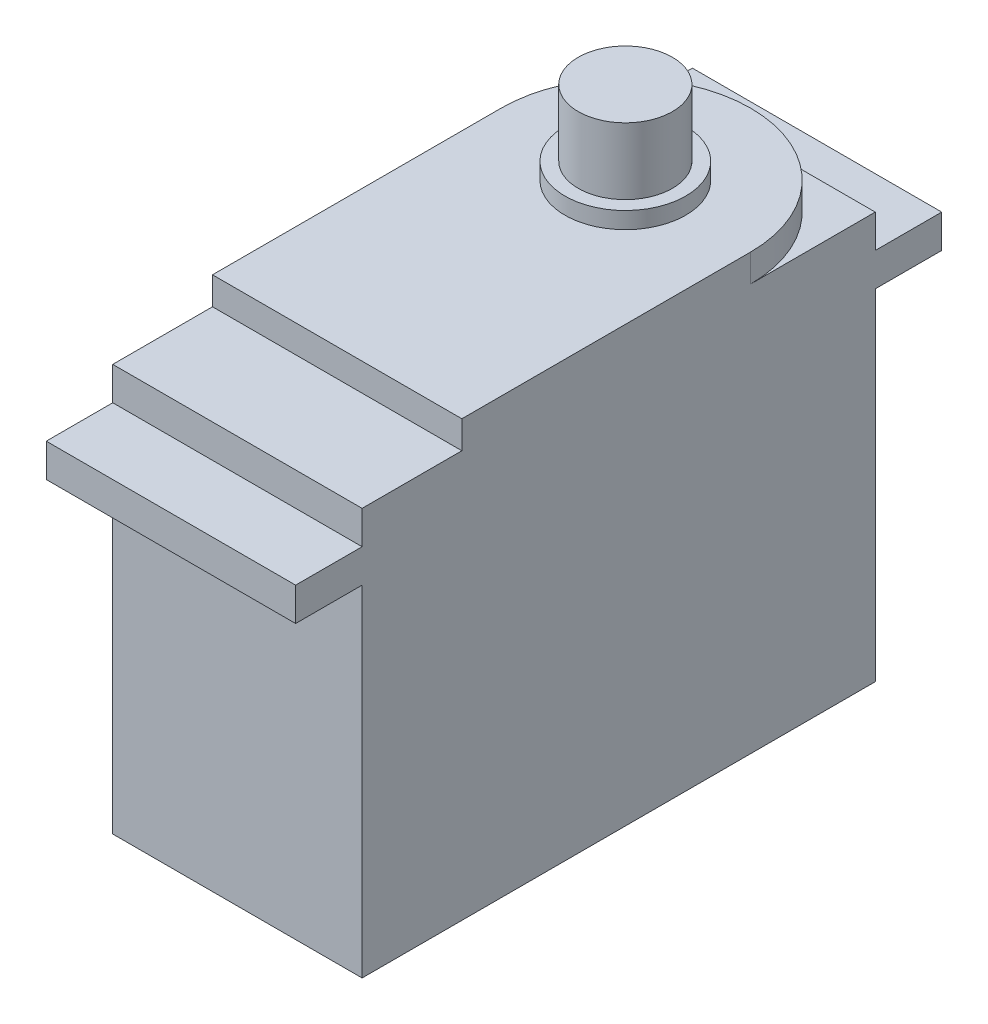
SolidWorks part; units mm, degrees
ref_plane "Front Plane" through (0, 0, 0) normal (0, 0, 1) x (1, 0, 0)
ref_plane "Top Plane" through (0, 0, 0) normal (0, 1, 0) x (1, 0, 0)
ref_plane "Right Plane" through (0, 0, 0) normal (1, 0, 0) x (0, 0, -1)
sketch "Sketch2" plane through (0, 0, 0) normal (0, 1, 0) x (1, 0, 0)
  line L1 (-14.2875, -29.4005) -> (14.2875, -29.4005)
  line L2 (-14.2875, -29.4005) -> (-14.2875, 29.4005)
  line L3 (-14.2875, 29.4005) -> (14.2875, 29.4005)
  line L4 (14.2875, -29.4005) -> (14.2875, 29.4005)
  line L5 (-14.2875, -29.4005) -> (14.2875, 29.4005) construction
  line L6 (-14.2875, 29.4005) -> (14.2875, -29.4005) construction
  point P0 (0, 0)
  dimension "D1" = 28.575
  dimension "D2" = 58.801
extrude "Boss-Extrude1" add sketch "Sketch2" along normal blind 46.609
sketch "Sketch3" plane through (0, 46.609, 0) normal (0, 1, 0) x (1, 0, 0)
  line L0 (14.2875, -29.4005) -> (14.2875, 29.4005) construction
  line L1 (-14.2875, -37.0205) -> (14.2875, -37.0205)
  line L2 (-14.2875, -37.0205) -> (-14.2875, 37.0205)
  line L3 (-14.2875, 37.0205) -> (14.2875, 37.0205)
  line L4 (14.2875, -37.0205) -> (14.2875, 37.0205)
  line L5 (-14.2875, -37.0205) -> (14.2875, 37.0205) construction
  line L6 (-14.2875, 37.0205) -> (14.2875, -37.0205) construction
  line L7 (-14.2875, -29.4005) -> (14.2875, -29.4005) construction
  point P0 (0, 0)
  dimension "D1" = 7.62
extrude "Boss-Extrude2" add sketch "Sketch3" against normal blind 3.81 from offset 3.81 offset against normal yes
sketch "Sketch4" plane through (0, 46.609, 0) normal (0, 1, 0) x (1, 0, 0)
  line L0 (-14.2875, 29.4005) -> (-14.2875, -29.4005) construction
  line L1 (14.2875, -29.4005) -> (14.2875, 29.4005) construction
  line L2 (14.2875, 29.4005) -> (-14.2875, 29.4005) construction
  line L3 (-14.2875, 15.113) -> (-14.2875, -17.9705)
  line L4 (-14.2875, -17.9705) -> (14.2875, -17.9705)
  line L5 (14.2875, -17.9705) -> (14.2875, 15.113)
  line L6 (-14.2875, -29.4005) -> (14.2875, -29.4005) construction
  arc A0 (-14.2875, 15.113) -> (14.2875, 15.113) centre (0, 15.113) cw
  dimension "D1" = 11.43
extrude "Boss-Extrude3" add sketch "Sketch4" along normal blind 3.175
sketch "Sketch5" plane through (0, 49.784, 0) normal (0, 1, 0) x (1, 0, 0)
  line L0 (-14.2875, -29.4005) -> (14.2875, -29.4005) construction
  line L1 (0, 15.0495) -> (0, -29.4005) construction
  circle A0 centre (0, 15.0495) radius 6.9215
  dimension "D2" = 13.843
  dimension "D1" = 44.45
extrude "Boss-Extrude4" add sketch "Sketch5" along normal blind 1.905
sketch "Sketch6" plane through (0, 51.689, 0) normal (0, 1, 0) x (1, 0, 0)
  circle A0 centre (0, 15.0495) radius 5.3975
  dimension "D1" = 10.795
extrude "Boss-Extrude5" add sketch "Sketch6" along normal blind 7.62
